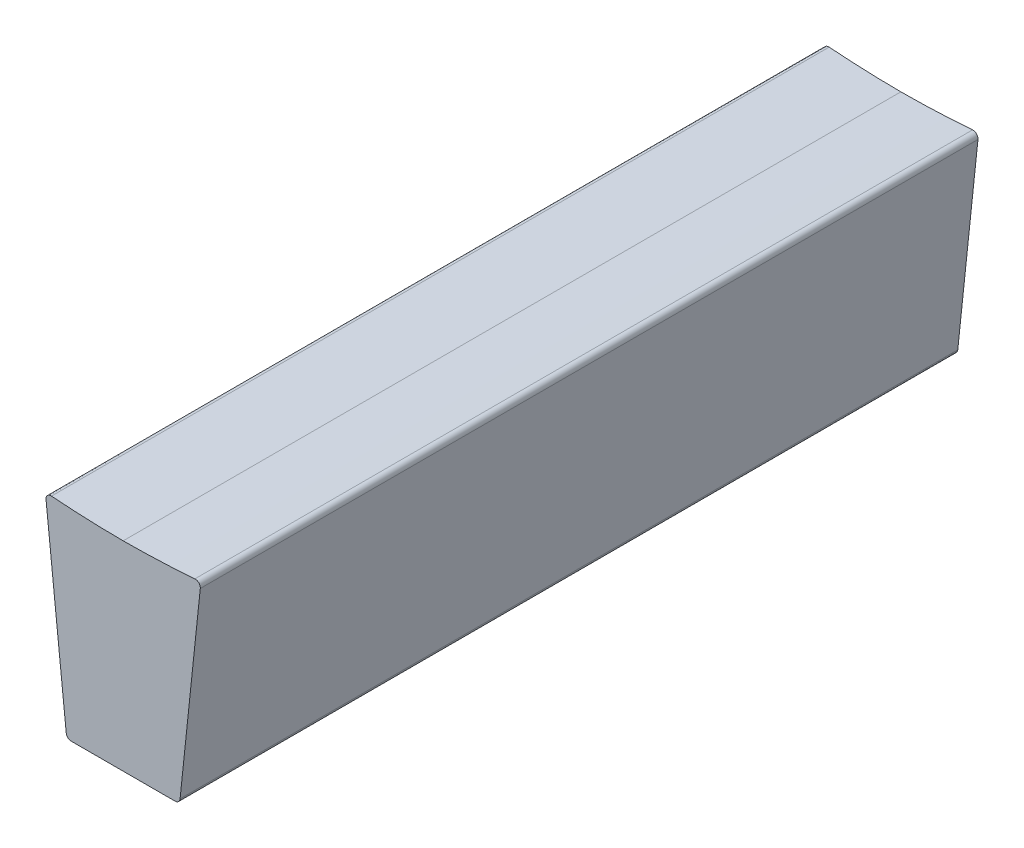
SolidWorks part; units mm, degrees
ref_plane "Front Plane" through (0, 0, 0) normal (0, 0, 1) x (1, 0, 0)
ref_plane "Top Plane" through (0, 0, 0) normal (0, 1, 0) x (1, 0, 0)
ref_plane "Right Plane" through (0, 0, 0) normal (1, 0, 0) x (0, 0, -1)
sketch "Sketch1" plane through (0, 0, 0) normal (0, 0, 1) x (1, 0, 0)
  line L0 (0, 0) -> (0, 51.796) construction
  line L1 (8.3469, 0) -> (-8.3469, 0)
  line L2 (-8.3469, 0) -> (-11.5, 30)
  line L3 (-11.5, 30) -> (0, 29.5) construction
  line L4 (-8.3469, 0) -> (-24.5489, 0) construction
  line L5 (8.3469, 0) -> (11.5, 30)
  arc A0 (-11.5, 30) -> (0, 29.5) centre (0.5579, 174.8326) ccw
  arc A1 (11.5, 30) -> (0, 29.5) centre (-0.5579, 174.8326) cw
  dimension "D5" = 145.3337
  dimension "D1" = 84
  dimension "D2" = 11.5
  dimension "D3" = 30
  dimension "D4" = 29.5
extrude "Boss-Extrude1" add sketch "Sketch1" against normal blind 115
fillet "Fillet1" radius 0.75 4 edges at (8.3469, 0, -57.5) (-8.3469, 0, -57.5) (11.5, 30, -57.5) (-11.5, 30, -57.5)
